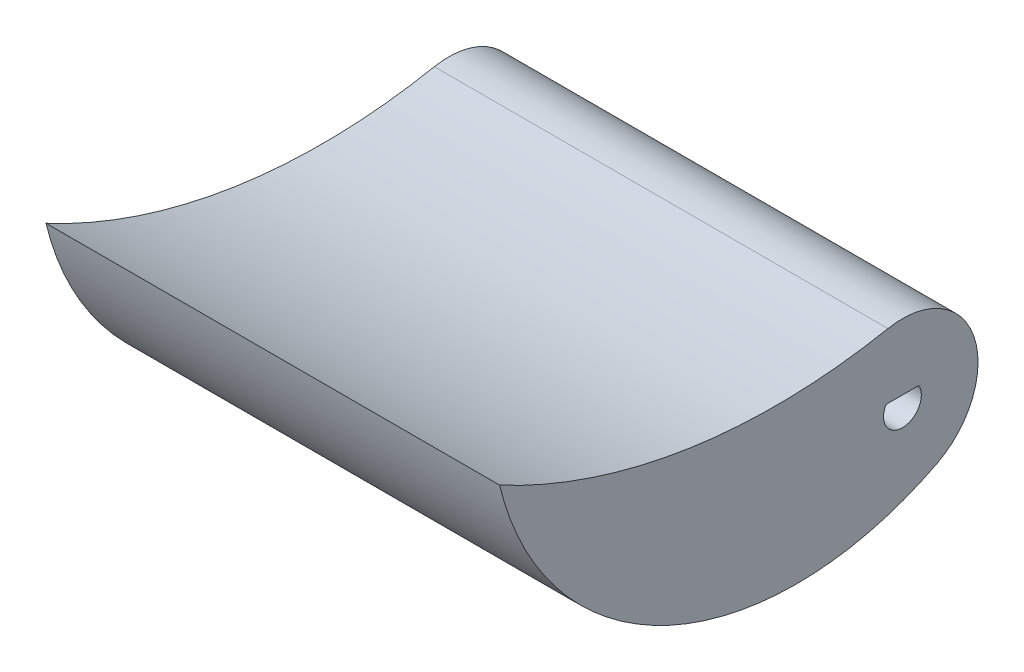
SolidWorks part; units mm, degrees
ref_plane "Front Plane" through (0, 0, 0) normal (0, 0, 1) x (1, 0, 0)
ref_plane "Top Plane" through (0, 0, 0) normal (0, 1, 0) x (1, 0, 0)
ref_plane "Right Plane" through (0, 0, 0) normal (1, 0, 0) x (0, 0, -1)
sketch "Sketch1" plane through (0, 0, 0) normal (1, 0, 0) x (0, 0, -1)
  line L1 (-5.4991, 3.1753) -> (5.4991, 3.1753)
  arc A0 (-4.8521, 24.9323) -> (11.6614, -22.5649) centre (0, 0) cw
  arc A1 (11.6614, -22.5649) -> (-135.3517, 44.6313) centre (-35.4948, 68.6829) cw
  arc A2 (-135.3517, 44.6313) -> (-4.8521, 24.9323) centre (-42.4362, 218.0575) ccw
  arc A4 (-5.4991, 3.1753) -> (5.4991, 3.1753) centre (0, 0) ccw
  dimension "D1" = 196.7484
  dimension "D2" = 102.7125
  dimension "D3" = 25.4
  dimension "D4" = 12.7
  dimension "D5" = 10.9982
  dimension "D6" = 11.6614
  dimension "D7" = 4.8521
extrude "Boss-Extrude1" add sketch "Sketch1" along normal mid plane 152.4
